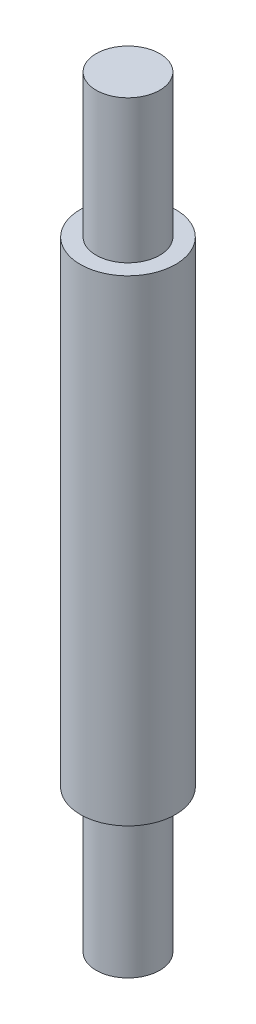
SolidWorks part; units mm, degrees
ref_plane "Front Plane" through (0, 0, 0) normal (1, 0, 0) x (0, 1, 0)
ref_plane "Top Plane" through (0, 0, 0) normal (0, 0, 1) x (0, 1, 0)
ref_plane "Right Plane" through (0, 0, 0) normal (0, 1, 0) x (-1, 0, 0)
sketch "Sketch1" plane through (0, 0, 0) normal (0, 1, 0) x (-1, 0, 0)
  circle A0 centre (0, 0) radius 15
  dimension "D1" = 30
extrude "Boss-Extrude1" add sketch "Sketch1" along normal mid plane 150
sketch "Sketch2" plane through (0, 75, 0) normal (0, 1, 0) x (-1, 0, 0)
  circle A0 centre (0, 0) radius 10
  dimension "D1" = 20
extrude "Boss-Extrude2" add sketch "Sketch2" along normal blind 45
mirror "Mirror1" about plane through (0, 0, 0) normal (0, 1, 0) of "Boss-Extrude2"
